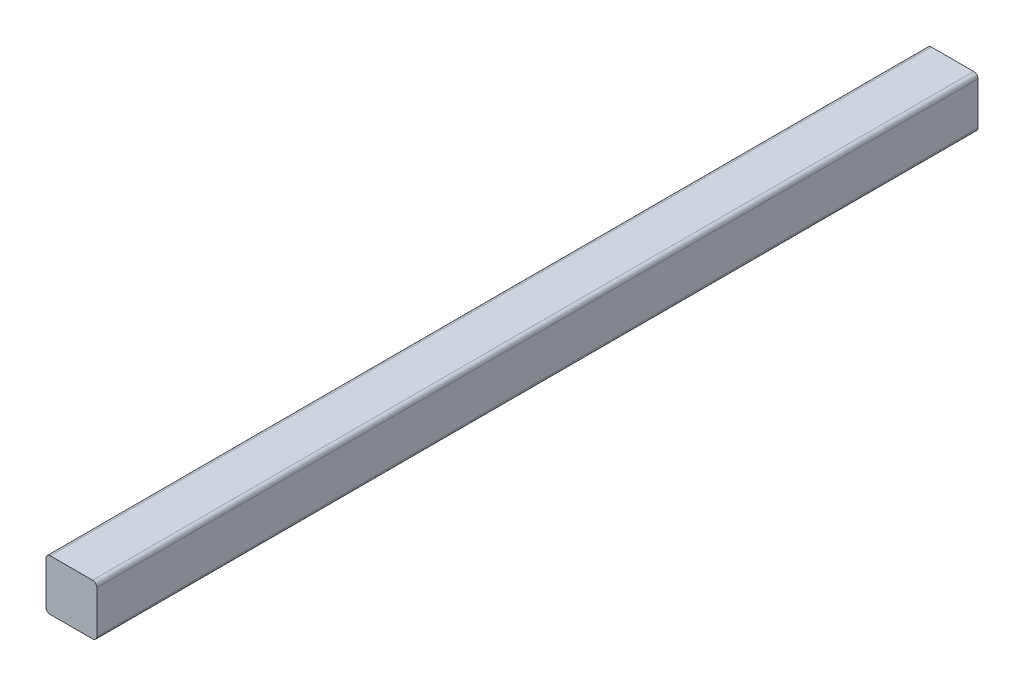
SolidWorks part; units mm, degrees
ref_plane "Front Plane" through (0, 0, 0) normal (0, 0, 1) x (1, 0, 0)
ref_plane "Top Plane" through (0, 0, 0) normal (0, 1, 0) x (1, 0, 0)
ref_plane "Right Plane" through (0, 0, 0) normal (1, 0, 0) x (0, 0, -1)
sketch "Sketch1" plane through (0, 0, 0) normal (0, 0, 1) x (1, 0, 0)
  line L1 (-19.05, -19.05) -> (19.05, -19.05)
  line L2 (-19.05, -19.05) -> (-19.05, 19.05)
  line L3 (-19.05, 19.05) -> (19.05, 19.05)
  line L4 (19.05, -19.05) -> (19.05, 19.05)
  line L5 (-19.05, -19.05) -> (19.05, 19.05) construction
  line L6 (-19.05, 19.05) -> (19.05, -19.05) construction
  point P0 (0, 0)
  dimension "D1" = 38.1
  dimension "D2" = 38.1
extrude "Boss-Extrude1" add sketch "Sketch1" along normal blind 660.4
fillet "Fillet1" radius 3.175 4 edges at (-19.05, 19.05, 330.2) (-19.05, -19.05, 330.2) (19.05, -19.05, 330.2) (19.05, 19.05, 330.2)
